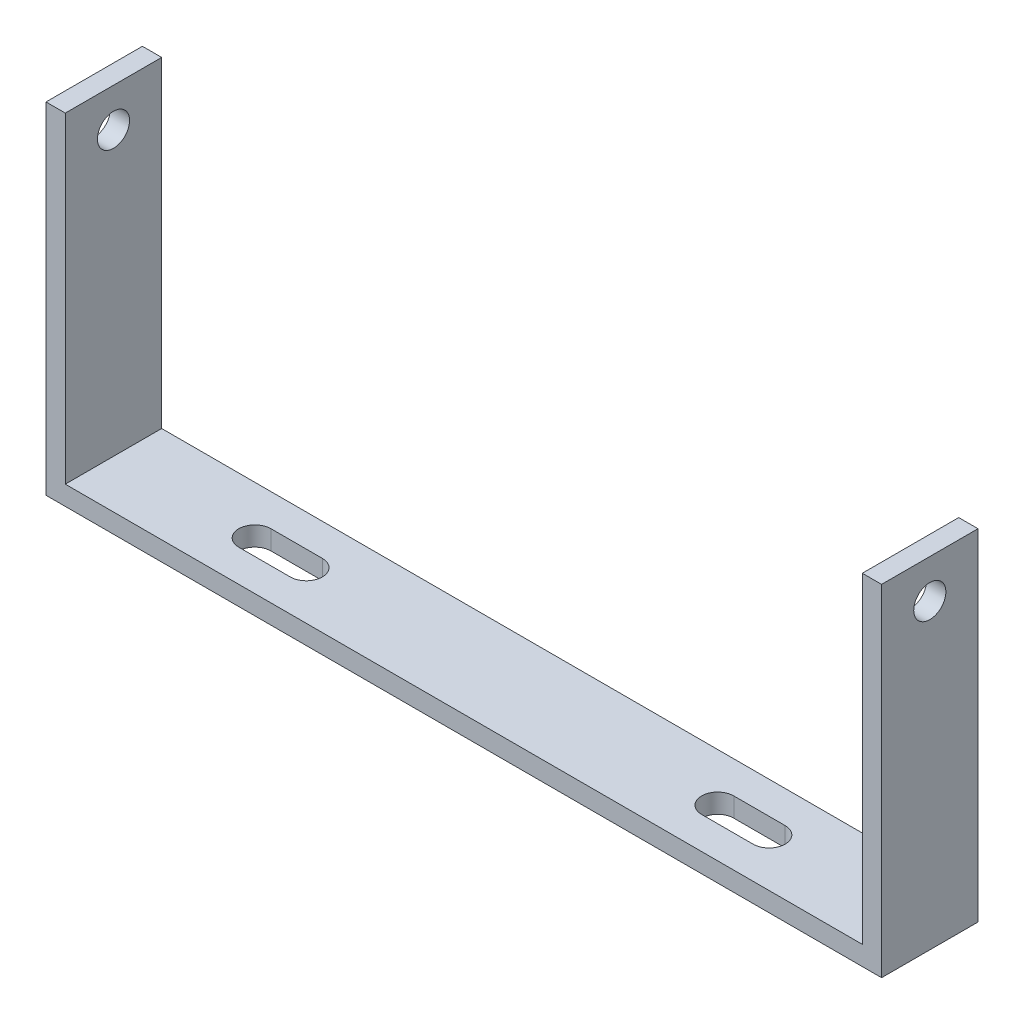
SolidWorks part; units mm, degrees
ref_plane "前视基准面" through (0, 0, 0) normal (0, 0, 1) x (1, 0, 0)
ref_plane "上视基准面" through (0, 0, 0) normal (0, 1, 0) x (1, 0, 0)
ref_plane "右视基准面" through (0, 0, 0) normal (1, 0, 0) x (0, 0, -1)
sketch "草图1" plane through (0, 0, 0) normal (0, 0, 1) x (1, 0, 0)
  line L0 (-31.2911, 0) -> (25.7961, 0) construction
  line L2 (0, 28.5055) -> (0, -28.2002) construction
sketch "草图2" plane through (0, 0, 0) normal (0, 1, 0) x (1, 0, 0)
  line L0 (0, 19.579) -> (0, -19.1113) construction
sketch "草图3" plane through (0, 0, 0) normal (0, 1, 0) x (1, 0, 0)
  line L1 (-65, 7.5) -> (65, 7.5)
  line L2 (-65, 7.5) -> (-65, -7.5)
  line L3 (-65, -7.5) -> (65, -7.5)
  line L4 (65, 7.5) -> (65, -7.5)
  line L6 (0, 26.2577) -> (0, -30.7423) construction
  line L7 (-112.4307, 0) -> (68.4582, 0) construction
  dimension "D1" = 15
  dimension "D2" = 130
extrude "凸台-拉伸1" add sketch "草图3" along normal blind 3
sketch "草图4" plane through (0, 3, 0) normal (0, 1, 0) x (1, 0, 0)
  line L0 (0, 19.579) -> (0, -19.1113) construction
  line L1 (0, -55) -> (0, 55) construction
  line L2 (-40, 2.5) -> (-32, 2.5)
  line L4 (-40, -2.5) -> (-32, -2.5)
  line L6 (40, -2.5) -> (32, -2.5)
  line L7 (40, 2.5) -> (32, 2.5)
  arc A0 (-40, 2.5) -> (-40, -2.5) centre (-40, 0) ccw
  arc A2 (-32, -2.5) -> (-32, 2.5) centre (-32, 0) ccw
  arc A3 (32, -2.5) -> (32, 2.5) centre (32, 0) cw
  arc A4 (40, 2.5) -> (40, -2.5) centre (40, 0) cw
  dimension "D1" = 40
  dimension "D2" = 8
extrude "切除-拉伸1" cut sketch "草图4" against normal blind 35
sketch "草图5" plane through (0, 3, 0) normal (0, 1, 0) x (1, 0, 0)
  line L0 (65, 7.5) -> (-65, 7.5) construction
  line L1 (-65, -7.5) -> (-62, -7.5)
  line L2 (-65, -7.5) -> (-65, 7.5)
  line L3 (-65, 7.5) -> (-62, 7.5)
  line L4 (-62, -7.5) -> (-62, 7.5)
  line L5 (0, -55) -> (0, 55) construction
  line L6 (62, -7.5) -> (62, 7.5)
  line L7 (65, 7.5) -> (62, 7.5)
  line L8 (65, -7.5) -> (65, 7.5)
  line L9 (65, -7.5) -> (62, -7.5)
  dimension "D1" = 3
extrude "凸台-拉伸2" add sketch "草图5" along normal blind 50
sketch "草图6" plane through (-65, 0, 0) normal (-1, 0, 0) x (0, 0, 1)
  line L0 (-7.5, 53) -> (7.5, 53) construction
  line L1 (-7.5, 0) -> (7.5, 0) construction
  circle A0 centre (0, 47) radius 2.5
  dimension "D1" = 6
extrude "切除-拉伸2" cut sketch "草图6" against normal blind 160
